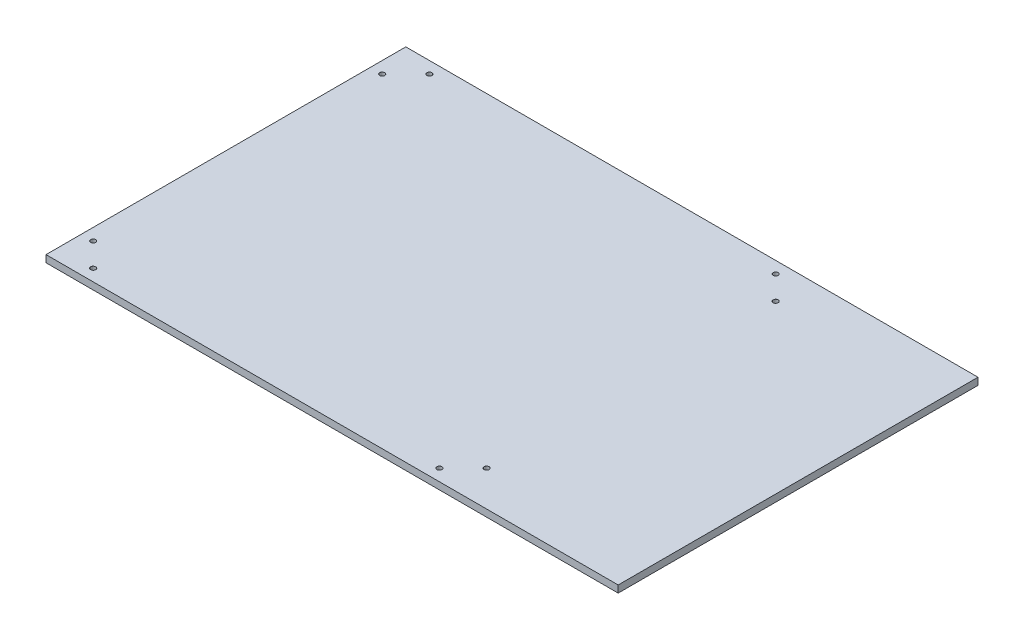
SolidWorks part; units mm, degrees
ref_plane "Front Plane" through (0, 0, 0) normal (0, 0, 1) x (1, 0, 0)
ref_plane "Top Plane" through (0, 0, 0) normal (0, 1, 0) x (1, 0, 0)
ref_plane "Right Plane" through (0, 0, 0) normal (1, 0, 0) x (0, 0, -1)
sketch "Sketch1" plane through (0, 0, 0) normal (0, 1, 0) x (1, 0, 0)
  line L1 (-677.3067, 361.6334) -> (292.6933, 361.6334)
  line L2 (-677.3067, 361.6334) -> (-677.3067, -248.3666)
  line L3 (-677.3067, -248.3666) -> (292.6933, -248.3666)
  line L4 (292.6933, 361.6334) -> (292.6933, -248.3666)
  dimension "D1" = 970
  dimension "D2" = 610
extrude "Boss-Extrude1" add sketch "Sketch1" along normal blind 12
sketch "Sketch2" plane through (0, 12, 0) normal (0, 1, 0) x (1, 0, 0)
  circle A0 centre (-30.2954, 341.622) radius 4.2339
extrude "Cut-Extrude1" cut sketch "Sketch2" against normal blind 10
sketch "Sketch3" plane through (0, 12, 0) normal (0, 1, 0) x (1, 0, 0)
  point P0 (0, 0)
  point P2 (-617.3067, 341.6334)
  point P6 (-657.3067, 301.6334)
  point P8 (-617.3067, -228.3666)
  point P10 (-657.3067, -188.3666)
  point P12 (9.6933, -188.3666)
  point P14 (-30.3067, -228.3666)
  point P16 (9.6933, 301.6334)
  point P18 (0, 0)
hole_wizard "Tap Drill for M10 Tap1" positions "Sketch3" profile "Sketch4" hole size "M10" standard "DIN" end condition up to next
sketch "Sketch4" plane through (-617.3067, 12, -341.6334) normal (1, 0, 0) x (0, 0, 1)
  line L0 (0, 0) -> (0, 12)
  line L1 (0, 12) -> (4.25, 12)
  line L2 (4.25, 12) -> (4.25, 0.025)
  line L3 (4.25, 0.025) -> (4.275, 0)
  line L5 (4.275, 0) -> (0, 0)
  line L6 (-4.25, 0.025) -> (-4.275, 0) construction
  line L11 (0, -6.35) -> (0, 107.95) construction
  dimension "Thru Hole Dia." = 8.5
  dimension "Thru Hole Depth" = 12
  dimension "Near C'Sink Dia." = 8.55
  dimension "Near C'Sink Angle" = 90
